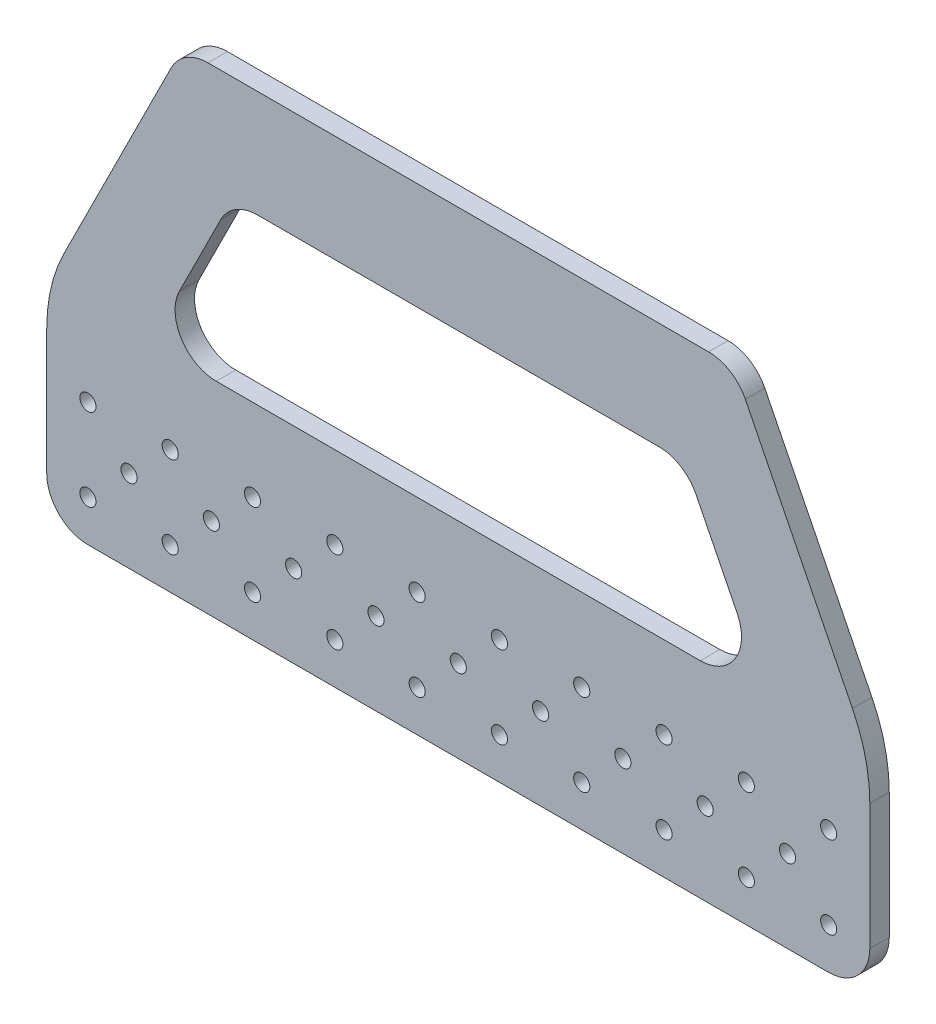
SolidWorks part; units mm, degrees
material "PC High Viscosity"
ref_plane "Front Plane" through (0, 0, 0) normal (0, 0, 1) x (1, 0, 0)
ref_plane "Top Plane" through (0, 0, 0) normal (0, 1, 0) x (1, 0, 0)
ref_plane "Right Plane" through (0, 0, 0) normal (1, 0, 0) x (0, 0, -1)
sketch "Sketch1" plane through (0, 0, 0) normal (0, 0, 1) x (1, 0, 0)
  line L0 (40.9398, 81.8796) -> (53.6398, 107.2796)
  line L1 (12.7, 0) -> (241.3, 0)
  line L2 (0, 12.7) -> (0, 51.5077)
  line L3 (52.299, 63.5) -> (201.701, 63.5)
  line L4 (254, 12.7) -> (254, 51.5077)
  line L5 (57.15, 63.5) -> (196.85, 63.5)
  line L6 (57.15, 63.5) -> (57.15, 114.3) construction
  line L7 (64.999, 114.3) -> (189.001, 114.3)
  line L8 (196.85, 63.5) -> (196.85, 114.3) construction
  line L9 (213.0602, 81.8796) -> (200.3602, 107.2796)
  line L10 (5.3631, 74.2262) -> (38.3998, 140.2996)
  line L11 (49.759, 147.32) -> (204.241, 147.32)
  line L12 (215.6002, 140.2996) -> (248.6369, 74.2262)
  line L13 (0, 63.5) -> (31.75, 63.5) construction
  line L14 (222.25, 63.5) -> (254, 63.5) construction
  arc A0 (204.241, 147.32) -> (215.6002, 140.2996) centre (204.241, 134.62) cw
  arc A1 (38.3998, 140.2996) -> (49.759, 147.32) centre (49.759, 134.62) cw
  arc A2 (189.001, 114.3) -> (200.3602, 107.2796) centre (189.001, 101.6) cw
  arc A3 (213.0602, 81.8796) -> (201.701, 63.5) centre (201.701, 76.2) cw
  arc A4 (40.9398, 81.8796) -> (52.299, 63.5) centre (52.299, 76.2) ccw
  arc A5 (53.6398, 107.2796) -> (64.999, 114.3) centre (64.999, 101.6) cw
  arc A6 (248.6369, 74.2262) -> (254, 51.5077) centre (203.2, 51.5077) cw
  arc A7 (0, 51.5077) -> (5.3631, 74.2262) centre (50.8, 51.5077) cw
  arc A8 (241.3, 0) -> (254, 12.7) centre (241.3, 12.7) ccw
  arc A9 (12.7, 0) -> (0, 12.7) centre (12.7, 12.7) cw
  point P40 (254, 0)
  point P43 (0, 0)
  dimension "D9" = 12.7
  dimension "D10" = 50.8
  dimension "D11" = 12.7
  dimension "D1" = 63.5
  dimension "D2" = 254
  dimension "D3" = 50.8
  dimension "D4" = 139.7
  dimension "D5" = 57.15
  dimension "D6" = 25.4
  dimension "D7" = 25.4
  dimension "D8" = 33.02
extrude "Boss-Extrude1" add sketch "Sketch1" along normal blind 6 contours A1 L10 L2 L1 L4 L12 A0 L11 L0 A5 L7 A2 L9 A3 L3 A4
sketch "Sketch2" plane through (0, 0, 6) normal (0, 0, 1) x (1, 0, 0)
  line L0 (12.7, 0) -> (241.3, 0) construction
  line L1 (254, 12.7) -> (254, 51.5077) construction
  line L2 (241.3, 12.7) -> (215.9, 12.7) construction
  line L3 (241.3, 12.7) -> (241.3, 38.1) construction
  line L4 (25.4, 25.4) -> (50.8, 25.4) construction
  circle A0 centre (241.3, 12.7) radius 2.4892
  circle A1 centre (215.9, 12.7) radius 2.4892
  circle A2 centre (190.5, 12.7) radius 2.4892
  circle A3 centre (165.1, 12.7) radius 2.4892
  circle A4 centre (139.7, 12.7) radius 2.4892
  circle A5 centre (114.3, 12.7) radius 2.4892
  circle A6 centre (88.9, 12.7) radius 2.4892
  circle A7 centre (63.5, 12.7) radius 2.4892
  circle A8 centre (38.1, 12.7) radius 2.4892
  circle A9 centre (12.7, 12.7) radius 2.4892
  circle A10 centre (215.9, 38.1) radius 2.4892
  circle A11 centre (190.5, 38.1) radius 2.4892
  circle A12 centre (165.1, 38.1) radius 2.4892
  circle A13 centre (139.7, 38.1) radius 2.4892
  circle A14 centre (114.3, 38.1) radius 2.4892
  circle A15 centre (88.9, 38.1) radius 2.4892
  circle A16 centre (63.5, 38.1) radius 2.4892
  circle A17 centre (38.1, 38.1) radius 2.4892
  circle A18 centre (12.7, 38.1) radius 2.4892
  circle A19 centre (241.3, 38.1) radius 2.4892
  circle A20 centre (25.4, 25.4) radius 2.4892
  circle A21 centre (50.8, 25.4) radius 2.4892
  circle A22 centre (76.2, 25.4) radius 2.4892
  circle A23 centre (101.6, 25.4) radius 2.4892
  circle A24 centre (127, 25.4) radius 2.4892
  circle A25 centre (152.4, 25.4) radius 2.4892
  circle A26 centre (177.8, 25.4) radius 2.4892
  circle A27 centre (203.2, 25.4) radius 2.4892
  circle A28 centre (228.6, 25.4) radius 2.4892
  dimension "D1" = 4.9784
  dimension "D2" = 12.7
  dimension "D3" = 12.7
  dimension "D8" = 12.7
  dimension "D9" = 12.7
  dimension "D6" = 25.4
  dimension "D7" = 25.4
  dimension "D11" = 25.4
  dimension "D4" = 10
  dimension "D5" = 2
  dimension "D10" = 9
extrude "Cut-Extrude1" cut sketch "Sketch2" against normal through all
